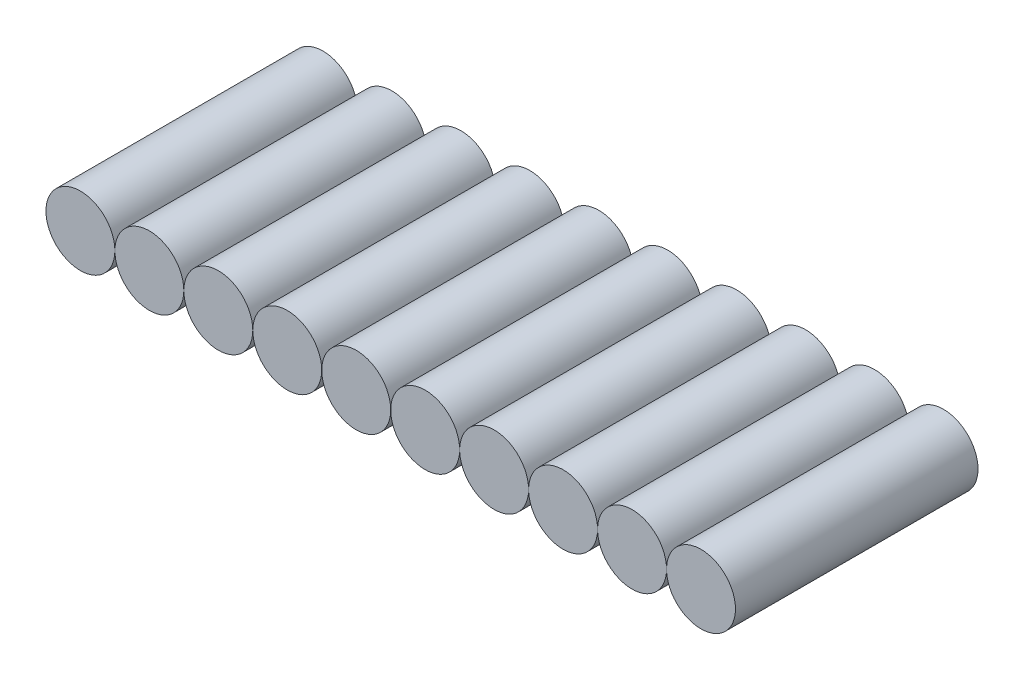
SolidWorks part; units mm, degrees
ref_plane "Plan de face" through (0, 0, 0) normal (0, 0, 1) x (1, 0, 0)
ref_plane "Plan de dessus" through (0, 0, 0) normal (0, 1, 0) x (1, 0, 0)
ref_plane "Plan de droite" through (0, 0, 0) normal (1, 0, 0) x (0, 0, -1)
sketch "Esquisse1" plane through (0, 0, 0) normal (0, 0, 1) x (1, 0, 0)
  circle A0 centre (0, 0) radius 7.25
  circle A1 centre (14.5, 0) radius 7.25
  circle A2 centre (29, 0) radius 7.25
  circle A3 centre (43.5, 0) radius 7.25
  circle A4 centre (58, 0) radius 7.25
  circle A5 centre (72.5, 0) radius 7.25
  circle A6 centre (87, 0) radius 7.25
  circle A7 centre (101.5, 0) radius 7.25
  circle A8 centre (116, 0) radius 7.25
  circle A9 centre (130.5, 0) radius 7.25
  dimension "D1" = 14.5
  dimension "D2" = 10
extrude "Boss.-Extru.1" add sketch "Esquisse1" along normal blind 51 contours A1 | A2 | A3 | A0 | A4 | A5 | A6 | A7 | A8 | A9
